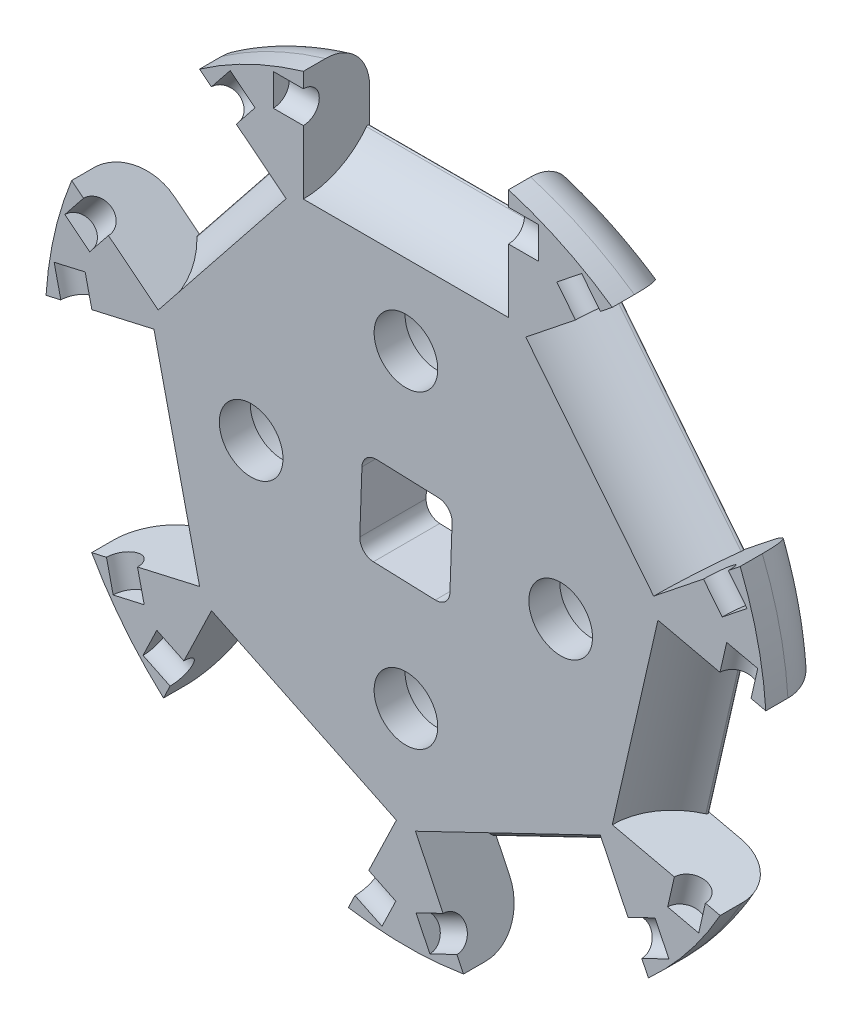
SolidWorks part; units mm, degrees
other "Markup1"
sketch "Sketch8" plane through (32.7336, 32.7336, 0) normal (0.5701, 0.1846, 0.8006) x (0.8043, 0.0736, -0.5897)
ref_plane "Front Plane" through (0, 0, 0) normal (0, 0, 1) x (1, 0, 0)
ref_plane "Top Plane" through (0, 0, 0) normal (0, 1, 0) x (1, 0, 0)
ref_plane "Right Plane" through (0, 0, 0) normal (1, 0, 0) x (0, 0, -1)
sketch "Sketch1" plane through (0, 0, 0) normal (0, 0, 1) x (1, 0, 0)
  circle A0 centre (0, 0) radius 25.8953
  dimension "D1" = 51.7906
extrude "Boss-Extrude2" add sketch "Sketch1" against normal blind 4.7625
fillet "Fillet1" radius 3.175 1 edges at (25.8953, 0, -4.7625)
sketch "Sketch2" plane through (0, 0, 0) normal (0, 0, 1) x (1, 0, 0)
  line L1 (-12.7, 25.8953) -> (12.7, 25.8953) construction
  line L2 (-7.366, 27.1653) -> (7.366, 27.1653)
  line L3 (-7.366, 27.1653) -> (-7.366, 16.7513)
  line L4 (-7.366, 16.7513) -> (7.366, 16.7513)
  line L5 (7.366, 27.1653) -> (7.366, 16.7513)
  line L6 (-7.366, 27.1653) -> (7.366, 16.7513) construction
  line L7 (-7.366, 16.7513) -> (7.366, 27.1653) construction
  line L35 (0, 0) -> (0, 25.8953) construction
  circle A1 centre (0, 0) radius 25.8953 construction
  point P10 (0, 21.9583)
  circle M7 centre (0, 0) radius 25.8953
  dimension "D1" = 14.732
  dimension "D2" = 10.414
  dimension "D3" = 1.27
  dimension "D4" = 25.4
extrude "Cut-Extrude2" cut sketch "Sketch2" against normal blind 12.7 contours L5 L3 L4 M7
pattern_circular "CirPattern1" count 7 over 360 about axis through (0, 0, 0) along (0, 0, 1) of "Cut-Extrude2"
ref_plane "Plane1" through (0, 0, 0) normal (1, 0, 0) x (0, 0, -1)
sketch "Sketch4" plane through (0, 0, 0) normal (1, 0, 0) x (0, 0, -1)
  line L0 (4.7625, 16.7513) -> (0, 16.7513) construction
  circle A0 centre (0, 22.5933) radius 1.143
  dimension "D1" = 2.286
  dimension "D2" = 5.842
extrude "Cut-Extrude4" cut sketch "Sketch4" against normal mid plane 19.05
pattern_circular "CirPattern2" count 7 over 360 about axis through (0, 0, 0) along (0, 0, 1) of "Cut-Extrude4"
sketch "Sketch5" plane through (0, 0, 0) normal (0, 0, 1) x (1, 0, 0)
  line L0 (-7.366, 16.7513) -> (7.366, 16.7513) construction
  line L1 (-3.3495, -3.1235) -> (3.1235, -3.3495)
  line L2 (-3.3495, -3.1235) -> (-3.1235, 3.3495)
  line L3 (-3.1235, 3.3495) -> (3.3495, 3.1235)
  line L4 (3.1235, -3.3495) -> (3.3495, 3.1235)
  line L5 (-3.3495, -3.1235) -> (3.3495, 3.1235) construction
  line L6 (-3.1235, 3.3495) -> (3.1235, -3.3495) construction
  point P0 (0, 0)
  point P6 (3.8795, 3.0728)
  dimension "D1" = 6.477
  dimension "D2" = 2
extrude "Cut-Extrude5" cut sketch "Sketch5" against normal through all
sketch "Sketch6" plane through (0, 0, -4.7625) normal (0, 0, -1) x (-1, 0, 0)
  line L1 (2.7339, 0) -> (-2.7339, 0) construction
  line L2 (0, 2.7339) -> (0, -2.7339) construction
  circle A0 centre (0, 11.1125) radius 2.286
  circle A1 centre (11.1125, 0) radius 2.286
  circle A2 centre (0, -11.1125) radius 2.286
  circle A3 centre (-11.1125, 0) radius 2.286
  dimension "D4" = 4.572
  dimension "D1" = 11.1125
  dimension "D2" = 11.1125
extrude "Cut-Extrude7" cut sketch "Sketch6" against normal through all
sketch "Sketch7" plane through (0, 0, -4.7625) normal (0, 0, -1) x (-1, 0, 0)
  circle A0 centre (-11.1125, 0) radius 4.445
  circle A1 centre (11.1125, 0) radius 4.445
  circle A2 centre (0, -11.1125) radius 4.445
  circle A3 centre (0, 11.1125) radius 4.445
  dimension "D2" = 8.89
extrude "Cut-Extrude8" cut sketch "Sketch7" against normal blind 2.54
sketch "Sketch10" plane through (7.366, 0, 0) normal (-1, 0, 0) x (0, 0, 1)
  line L0 (-4.7625, 21.4931) -> (-4.7625, 16.7513) construction
  line L1 (-4.7625, 16.7513) -> (0, 16.7513)
  line L2 (-4.7625, 16.7513) -> (-4.7625, 19.4342)
  line L4 (0, 16.7513) -> (0, 16.8783)
  arc A0 (-4.7625, 19.4342) -> (0, 16.8783) centre (0, 22.5933) ccw
  dimension "D1" = 11.43
  dimension "D2" = 4.7625
extrude "Boss-Extrude4" add sketch "Sketch10" along normal up to next
fillet "Fillet2" radius 0.127 1 edges at (0, 19.4342, -4.7625)
pattern_circular "CirPattern5" count 7 over 360 about axis through (0, 0, 0) along (0, 0, 1) of "Boss-Extrude4", "Fillet2"
fillet "Fillet3" radius 1.016 4 edges at (3.1235, -3.3495, -2.3813) (3.3495, 3.1235, -2.3813) (-3.1235, 3.3495, -2.3813) (-3.3495, -3.1235, -2.3813)
